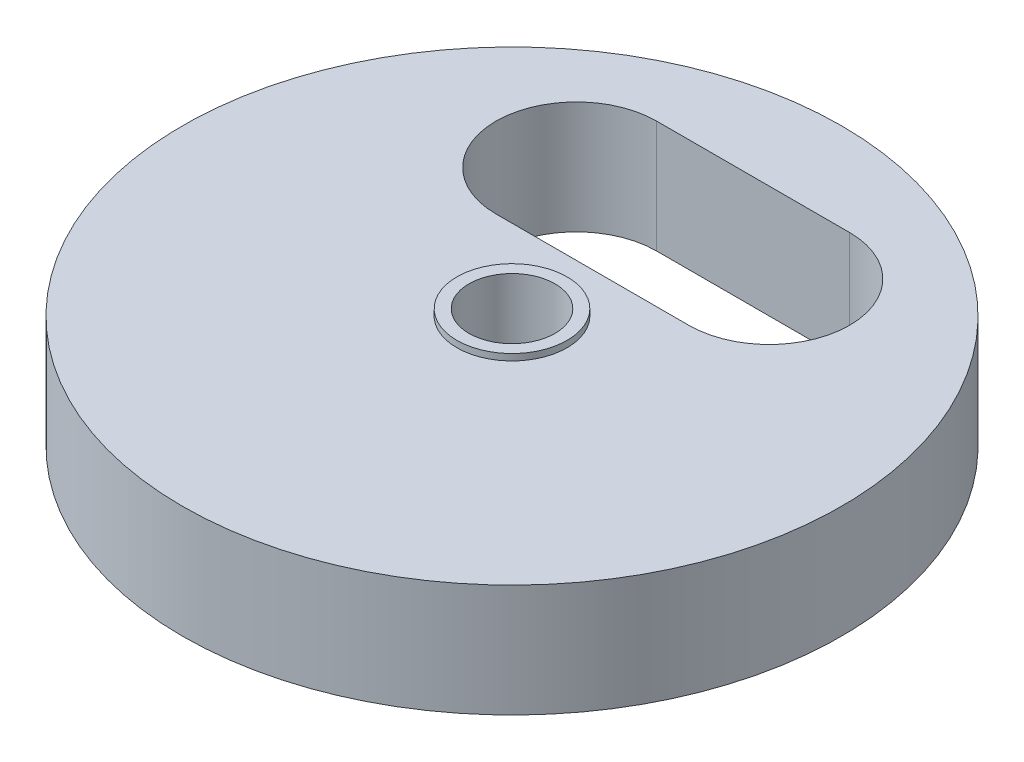
SolidWorks part; units mm, degrees
ref_plane "Front Plane" through (0, 0, 0) normal (0, 0, 1) x (1, 0, 0)
ref_plane "Top Plane" through (0, 0, 0) normal (0, 1, 0) x (1, 0, 0)
ref_plane "Right Plane" through (0, 0, 0) normal (1, 0, 0) x (0, 0, -1)
sketch "Sketch1" plane through (0, 0, 0) normal (0, 1, 0) x (1, 0, 0)
  circle A0 centre (0, 0) radius 20.5
  dimension "D1" = 41
extrude "Boss-Extrude1" add sketch "Sketch1" along normal blind 7
sketch "Sketch2" plane through (0, 7, 0) normal (0, 1, 0) x (1, 0, 0)
  circle A0 centre (0, 0) radius 2.675
  dimension "D1" = 5.35
extrude "Cut-Extrude1" cut sketch "Sketch2" against normal blind 7
sketch "Sketch3" plane through (0, 7, 0) normal (0, 1, 0) x (1, 0, 0)
  circle A0 centre (0, 0) radius 3.425
  circle A1 centre (0, 0) radius 2.675
  dimension "D1" = 5.35
  dimension "D2" = 6.85
extrude "Boss-Extrude2" add sketch "Sketch3" along normal blind 0.4
sketch "Sketch5" plane through (0, 7, 0) normal (0, 1, 0) x (1, 0, 0)
  line L0 (-6, 15) -> (6, 15)
  line L1 (-6, 5) -> (6, 5)
  arc A1 (-6, 15) -> (-6, 5) centre (-6, 10) ccw
  arc A2 (6, 5) -> (6, 15) centre (6, 10) ccw
  dimension "D1" = 12
  dimension "D2" = 6
  dimension "D3" = 10
  dimension "D4" = 10
  dimension "D5" = 10
  dimension "D6" = 10
extrude "Cut-Extrude3" cut sketch "Sketch5" against normal blind 7
